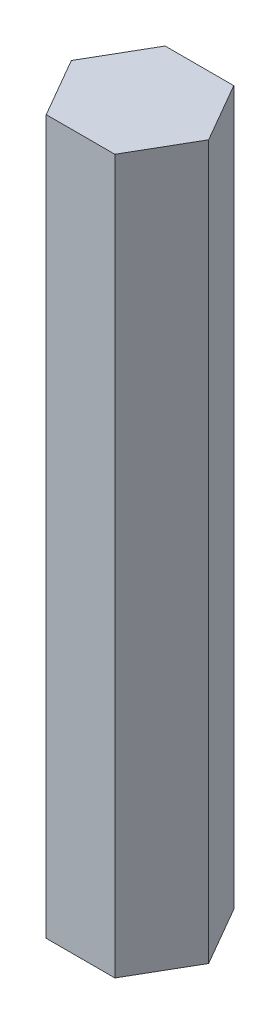
SolidWorks part; units mm, degrees
ref_plane "Front Plane" through (0, 0, 0) normal (0, 0, 1) x (1, 0, 0)
ref_plane "Top Plane" through (0, 0, 0) normal (0, 1, 0) x (1, 0, 0)
ref_plane "Right Plane" through (0, 0, 0) normal (1, 0, 0) x (0, 0, -1)
sketch "Sketch1" plane through (0, 0, 0) normal (0, 1, 0) x (1, 0, 0)
  line L1 (3.6662, 6.35) -> (-3.6662, 6.35)
  line L2 (-3.6662, 6.35) -> (-7.3323, 0)
  line L3 (-7.3323, 0) -> (-3.6662, -6.35)
  line L4 (-3.6662, -6.35) -> (3.6662, -6.35)
  line L5 (3.6662, -6.35) -> (7.3323, 0)
  line L6 (7.3323, 0) -> (3.6662, 6.35)
  circle A0 centre (0, 0) radius 6.35 construction
  dimension "D1" = 12.7
extrude "Boss-Extrude1" add sketch "Sketch1" along normal mid plane 76.2
